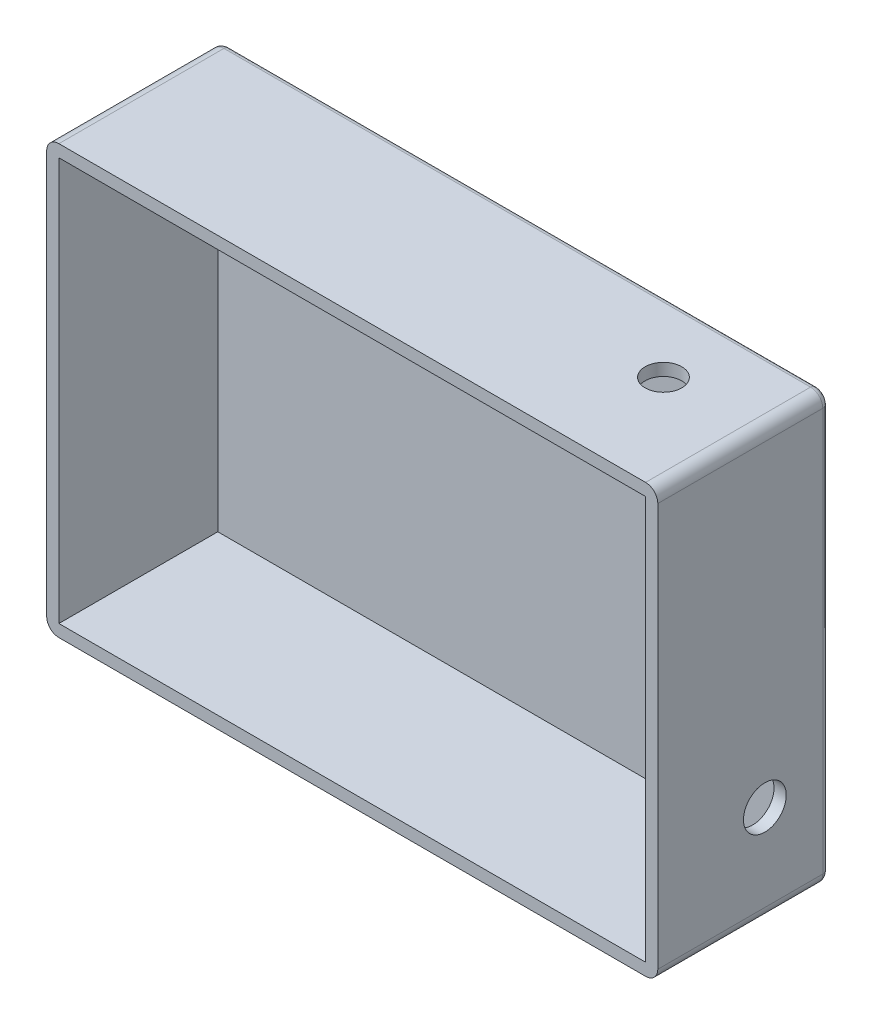
SolidWorks part; units mm, degrees
ref_plane "Front Plane" through (0, 0, 0) normal (0, 0, 1) x (1, 0, 0)
ref_plane "Top Plane" through (0, 0, 0) normal (0, 1, 0) x (1, 0, 0)
ref_plane "Right Plane" through (0, 0, 0) normal (1, 0, 0) x (0, 0, -1)
sketch "Sketch1" plane through (0, 0, 0) normal (0, 0, 1) x (1, 0, 0)
  line L1 (-250, 175) -> (250, 175)
  line L2 (-250, 175) -> (-250, -175)
  line L3 (-250, -175) -> (250, -175)
  line L4 (250, 175) -> (250, -175)
  line L5 (-250, 175) -> (250, -175) construction
  line L6 (-250, -175) -> (250, 175) construction
  point P0 (0, 0)
  dimension "D1" = 500
  dimension "D2" = 350
extrude "Boss-Extrude2" add sketch "Sketch1" along normal blind 140
sketch "Sketch2" plane through (250, 0, 0) normal (1, 0, 0) x (0, 0, -1)
  circle A0 centre (-52.4033, -94.104) radius 17.5
  dimension "D1" = 35
extrude "Cut-Extrude1" cut sketch "Sketch2" against normal blind 10
sketch "Sketch3" plane through (0, 175, 0) normal (0, 1, 0) x (1, 0, 0)
  circle A0 centre (172.8642, -58.2461) radius 15
  dimension "D1" = 30
extrude "Cut-Extrude2" cut sketch "Sketch3" against normal blind 10
sketch "Sketch4" plane through (0, 0, 140) normal (0, 0, 1) x (1, 0, 0)
  line L0 (-250, 175) -> (-250, -175) construction
  line L1 (-240, 165) -> (240, 165)
  line L2 (-240, 165) -> (-240, -165)
  line L3 (-240, -165) -> (240, -165)
  line L4 (240, 165) -> (240, -165)
  line L5 (-240, 165) -> (240, -165) construction
  line L6 (-240, -165) -> (240, 165) construction
  line L7 (250, 175) -> (-250, 175) construction
  point P0 (0, 0)
  dimension "D1" = 10
  dimension "D2" = 10
extrude "Cut-Extrude3" cut sketch "Sketch4" against normal blind 130
fillet "Fillet1" radius 10 4 edges at (250, 175, 70) (250, -175, 70) (-250, 175, 70) (-250, -175, 70)
fillet "Fillet3" radius 5 8 edges at (247.0711, 172.0711, 0) (250, 0, 0) (247.0711, -172.0711, 0) (0, -175, 0) (-247.0711, -172.0711, 0) (-250, 0, 0) (-247.0711, 172.0711, 0) (0, 175, 0)
